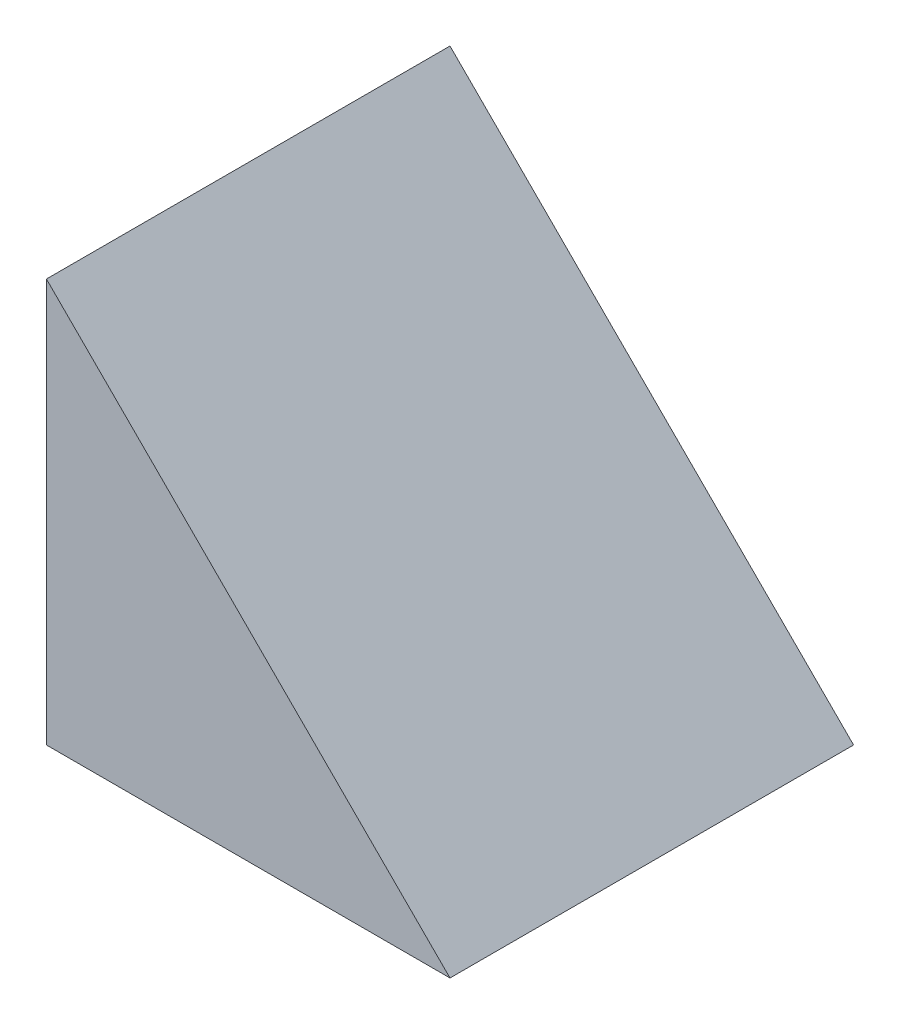
SolidWorks part; units mm, degrees
ref_plane "Front Plane" through (0, 0, 0) normal (0, 0, 1) x (1, 0, 0)
ref_plane "Top Plane" through (0, 0, 0) normal (0, 1, 0) x (1, 0, 0)
ref_plane "Right Plane" through (0, 0, 0) normal (1, 0, 0) x (0, 0, -1)
sketch "草图1" plane through (0, 0, 0) normal (0, 0, 1) x (1, 0, 0)
  line L0 (-30.4256, 46.9697) -> (-30.4256, -53.0303)
  line L1 (-30.4256, -53.0303) -> (69.5744, -53.0303)
  line L2 (69.5744, -53.0303) -> (-30.4256, 46.9697)
  dimension "D1" = 100
  dimension "D2" = 100
extrude "凸台-拉伸1" add sketch "草图1" along normal mid plane 100
